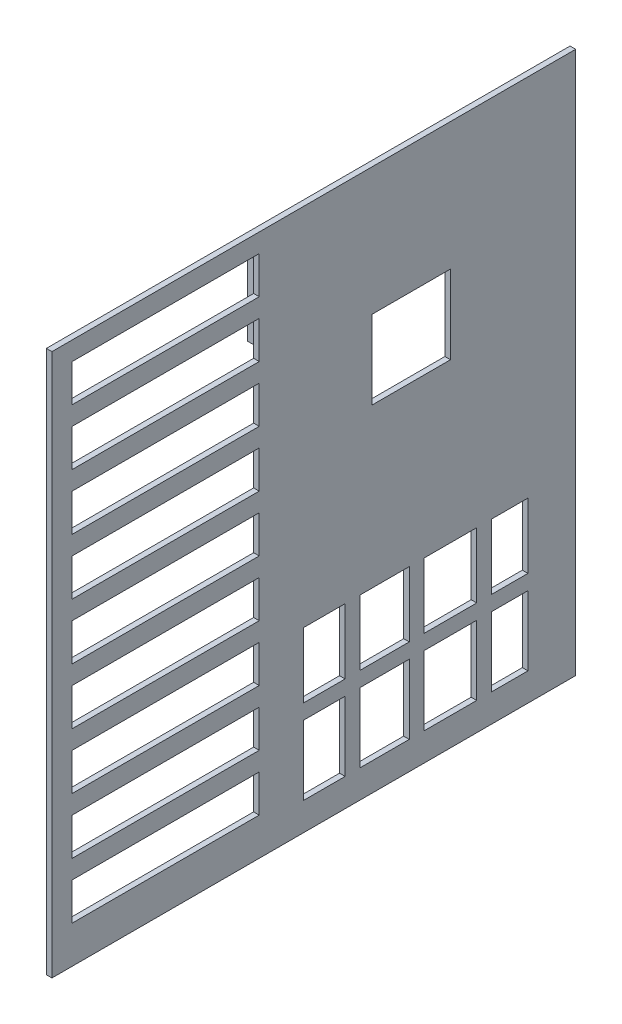
SolidWorks part; units mm, degrees
ref_plane "前视基准面" through (0, 0, 0) normal (0, 0, 1) x (1, 0, 0)
ref_plane "上视基准面" through (0, 0, 0) normal (0, 1, 0) x (1, 0, 0)
ref_plane "右视基准面" through (0, 0, 0) normal (1, 0, 0) x (0, 0, -1)
other "Configuration Table"
sketch "草图1" plane through (0, 0, 0) normal (1, 0, 0) x (0, 0, -1)
  line L1 (-38.0706, 40.3861) -> (241.9294, 40.3861)
  line L2 (-38.0706, 40.3861) -> (-38.0706, -249.6139)
  line L3 (-38.0706, -249.6139) -> (241.9294, -249.6139)
  line L4 (241.9294, 40.3861) -> (241.9294, -249.6139)
  dimension "D1" = 290
  dimension "D2" = 280
extrude "凸台-拉伸1" add sketch "草图1" along normal blind 3
sketch "草图2" plane through (0, 0, 0) normal (-1, 0, 0) x (0, 0, 1)
  line L1 (-175.0177, -27.9074) -> (-133.0177, -27.9074)
  line L2 (-175.0177, -27.9074) -> (-175.0177, -69.9074)
  line L3 (-175.0177, -69.9074) -> (-133.0177, -69.9074)
  line L4 (-133.0177, -27.9074) -> (-133.0177, -69.9074)
  dimension "D1" = 42
extrude "切除-拉伸1" cut sketch "草图2" against normal blind 3
sketch "草图3" plane through (0, 0, 0) normal (-1, 0, 0) x (0, 0, 1)
  line L1 (-216.5036, 9.932) -> (-94.5036, 9.932)
  line L2 (-216.5036, 9.932) -> (-216.5036, -110.068)
  line L3 (-216.5036, -110.068) -> (-94.5036, -110.068)
  line L4 (-94.5036, 9.932) -> (-94.5036, -110.068)
  line L5 (-216.5036, -110.068) -> (-94.5036, -110.068)
  line L6 (-216.5036, -110.068) -> (-216.5036, -120.068)
  line L7 (-216.5036, -120.068) -> (-94.5036, -120.068)
  line L8 (-94.5036, -110.068) -> (-94.5036, -120.068)
  dimension "D1" = 120
  dimension "D2" = 122
  dimension "D3" = 10
  dimension "D4" = 122
extrude "凸台-拉伸4" add sketch "草图3" along normal blind 20 contours L8 L3 L6 L7
sketch "草图5" plane through (0, 0, 0) normal (-1, 0, 0) x (0, 0, 1)
  line L1 (-216.5036, -110.068) -> (-221.5036, -110.068)
  line L2 (-216.5036, -110.068) -> (-216.5036, 9.932)
  line L3 (-216.5036, 9.932) -> (-221.5036, 9.932)
  line L4 (-221.5036, -110.068) -> (-221.5036, 9.932)
  line L5 (-94.5036, -110.068) -> (-89.5036, -110.068)
  line L6 (-94.5036, -110.068) -> (-94.5036, 9.932)
  line L7 (-94.5036, 9.932) -> (-89.5036, 9.932)
  line L8 (-89.5036, -110.068) -> (-89.5036, 9.932)
  line L9 (-221.5036, 9.932) -> (-216.5036, 9.932)
  line L10 (-221.5036, 9.932) -> (-221.5036, -30.068)
  line L11 (-221.5036, -30.068) -> (-216.5036, -30.068)
  line L12 (-216.5036, 9.932) -> (-216.5036, -30.068)
  line L13 (-94.5036, 9.932) -> (-89.5036, 9.932)
  line L14 (-94.5036, 9.932) -> (-94.5036, -30.068)
  line L15 (-94.5036, -30.068) -> (-89.5036, -30.068)
  line L16 (-89.5036, 9.932) -> (-89.5036, -30.068)
  dimension "D1" = 120
  dimension "D2" = 5
  dimension "D3" = 120
  dimension "D4" = 5
  dimension "D5" = 40
  dimension "D6" = 5
  dimension "D7" = 40
  dimension "D8" = 5
extrude "凸台-拉伸7" add sketch "草图5" along normal blind 20 contours L4 L11 L2 L3 | L6 L15 L8 L7
sketch "草图6" plane through (0, 0, -94.5036) normal (0, 0, 1) x (1, 0, 0)
  line L0 (-20, -120.068) -> (0, -120.068)
  line L1 (-20, -120.068) -> (0, -120.068) construction
  line L2 (0, -120.068) -> (0, -140.068)
  line L4 (0, 40.3861) -> (0, -249.6139) construction
  line L5 (0, -140.068) -> (-20, -120.068)
extrude "凸台-拉伸8" add sketch "草图6" against normal blind 10
pattern_linear "阵列(线性)1" count 4 spacing 37.3 along (0, 0, -1) of "凸台-拉伸8"
sketch "草图7" plane through (0, 0, 0) normal (-1, 0, 0) x (0, 0, 1)
  line L1 (38.0706, 40.3861) -> (-81.9294, 40.3861)
  line L2 (38.0706, 40.3861) -> (38.0706, -249.6139)
  line L3 (38.0706, -249.6139) -> (-81.9294, -249.6139)
  line L4 (-81.9294, 40.3861) -> (-81.9294, -249.6139)
  line L5 (38.0706, -249.6139) -> (-241.9294, -249.6139) construction
  line L7 (-72.7583, 30.3861) -> (27.2417, 30.3861)
  line L8 (-72.7583, 30.3861) -> (-72.7583, 10.3861)
  line L9 (-72.7583, 10.3861) -> (27.2417, 10.3861)
  line L10 (27.2417, 30.3861) -> (27.2417, 10.3861)
  dimension "D1" = 290
  dimension "D2" = 120
  dimension "D3" = 20
  dimension "D4" = 100
  dimension "D5" = 10
extrude "切除-拉伸3" cut sketch "草图7" against normal blind 3 contours L10 L7 L8 L9
pattern_linear "阵列(线性)2" count 9 spacing 30 along (0, -1, 0) of "切除-拉伸3"
sketch "草图8" plane through (0, 0, 0) normal (-1, 0, 0) x (0, 0, 1)
  line L0 (-216.4036, -120.068) -> (-216.4036, -140.068) construction
  line L1 (-216.4036, -154.6555) -> (-96.4036, -154.6555)
  line L2 (-216.4036, -154.6555) -> (-216.4036, -234.6555)
  line L3 (-216.4036, -234.6555) -> (-96.4036, -234.6555)
  line L4 (-96.4036, -154.6555) -> (-96.4036, -234.6555)
  line L6 (-216.4036, -189.5257) -> (-96.4036, -189.5257)
  line L7 (-216.4036, -189.5257) -> (-216.4036, -197.5257)
  line L8 (-216.4036, -197.5257) -> (-96.4036, -197.5257)
  line L9 (-96.4036, -189.5257) -> (-96.4036, -197.5257)
  line L10 (-126.6803, -154.6555) -> (-118.6803, -154.6555)
  line L11 (-126.6803, -154.6555) -> (-126.6803, -234.6555)
  line L12 (-126.6803, -234.6555) -> (-118.6803, -234.6555)
  line L13 (-118.6803, -154.6555) -> (-118.6803, -234.6555)
  line L14 (-197.0312, -154.6555) -> (-189.0312, -154.6555)
  line L15 (-197.0312, -154.6555) -> (-197.0312, -234.6555)
  line L16 (-197.0312, -234.6555) -> (-189.0312, -234.6555)
  line L17 (-189.0312, -154.6555) -> (-189.0312, -234.6555)
  line L18 (-160.9708, -154.6555) -> (-152.9708, -154.6555)
  line L19 (-160.9708, -154.6555) -> (-160.9708, -234.6555)
  line L20 (-160.9708, -234.6555) -> (-152.9708, -234.6555)
  line L21 (-152.9708, -154.6555) -> (-152.9708, -234.6555)
  dimension "D1" = 80
  dimension "D2" = 120
  dimension "D3" = 0
  dimension "D4" = 8
  dimension "D5" = 120
  dimension "D6" = 80
  dimension "D7" = 8
  dimension "D8" = 80
  dimension "D9" = 8
  dimension "D10" = 80
  dimension "D11" = 8
extrude "切除-拉伸4" cut sketch "草图8" against normal blind 3 contours L15 L1 L2 L6 | L19 L1 L17 L6 | L1 L21 L6 L11 | L1 L13 L6 L4 | L8 L13 L3 L4 | L8 L21 L3 L11 | L19 L8 L17 L3 | L15 L8 L2 L3
